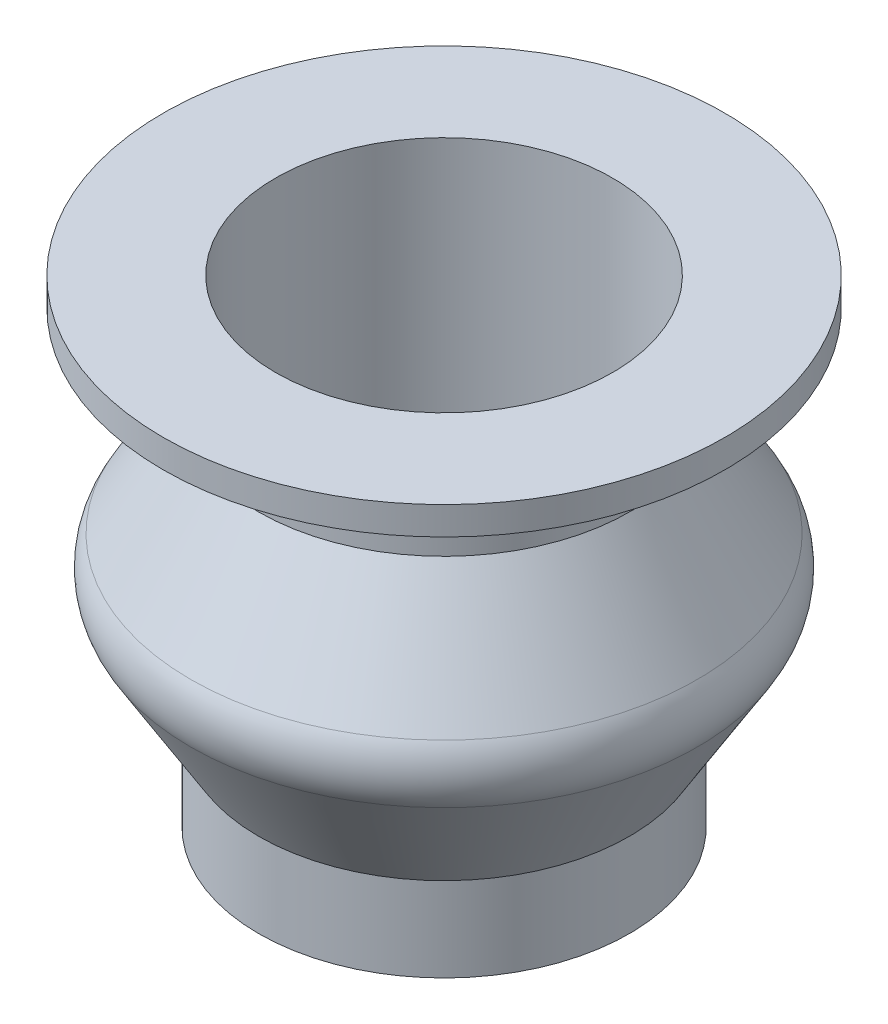
SolidWorks part; units mm, degrees
ref_plane "Front Plane" through (0, 0, 0) normal (0, 0, 1) x (1, 0, 0)
ref_plane "Top Plane" through (0, 0, 0) normal (0, 1, 0) x (1, 0, 0)
ref_plane "Right Plane" through (0, 0, 0) normal (1, 0, 0) x (0, 0, -1)
sketch "Sketch1" plane through (0, 0, 0) normal (0, 0, 1) x (1, 0, 0)
  line L0 (0, 78.9326) -> (0, -67.9775) construction
  line L1 (-88.764, 0) -> (65.7303, 0) construction
  line L2 (0, 45) -> (-50, 45)
  line L3 (-50, 45) -> (-50, 40)
  line L4 (-50, 40) -> (-35, 40)
  line L5 (-33, 25) -> (-48.7272, -0.781) construction
  line L6 (-35, 35) -> (-33, 35)
  line L7 (-33, -25) -> (-45.0738, -5.2078)
  line L8 (-33, 35) -> (-33, 25)
  line L9 (-35, 40) -> (-35, 35)
  line L10 (-35, 40) -> (-35, 25.5619) construction
  line L11 (-33, 25) -> (-45.0738, 5.2078)
  line L12 (-35, 25.5619) -> (-50.4346, 0.2605) construction
  line L13 (-33, 40) -> (-33, 25) construction
  line L14 (-33, -25) -> (-33, -40)
  line L15 (-33, -40) -> (0, -40)
  line L20 (0, 45) -> (0, -40)
  arc A0 (-45.0738, -5.2078) -> (-45.0738, 5.2078) centre (-36.5369, 0) cw
  point P13 (-50, 42.5)
  point P28 (-48.2507, 0)
  dimension "D8" = 10
  dimension "D1" = 50
  dimension "D2" = 25
  dimension "D3" = 48.2507
  dimension "D4" = 33
  dimension "D5" = 45
  dimension "D6" = 40
  dimension "D7" = 35
  dimension "D9" = 15
  dimension "D10" = 35
revolve "Revolve1" add sketch "Sketch1" angle 360 about L0
ref_plane "Plane1" through (0, 35, 0) normal (0, 1, 0) x (1, 0, 0)
sketch "Sketch2" plane through (0, 35, 0) normal (0, 1, 0) x (1, 0, 0)
  line L0 (0, 52.073) -> (0, -56.7416) construction
  line L1 (-55.0886, 0) -> (70.6829, 0) construction
  line L2 (-5, 36.6606) -> (-5, 34.641)
  line L3 (5, 36.6606) -> (5, 34.641)
  arc A0 (5, 34.641) -> (-5, 34.641) centre (0, 0) ccw
  arc A1 (5, 36.6606) -> (-5, 36.6606) centre (0, 0) ccw
  circle A3 centre (0, 0) radius 35 construction
  circle A4 centre (0, 0) radius 37 construction
  point P1 (37, 0)
  point P10 (33.4707, 10.233)
  dimension "D1" = 70
  dimension "D3" = 5
  dimension "D2" = 2
sketch "Sketch3" plane through (0, 0, 0) normal (0, 1, 0) x (1, 0, 0)
  circle A0 centre (0, 0) radius 30
  dimension "D1" = 60
extrude "Cut-Extrude1" cut sketch "Sketch3" against normal through all both and the other way through all
